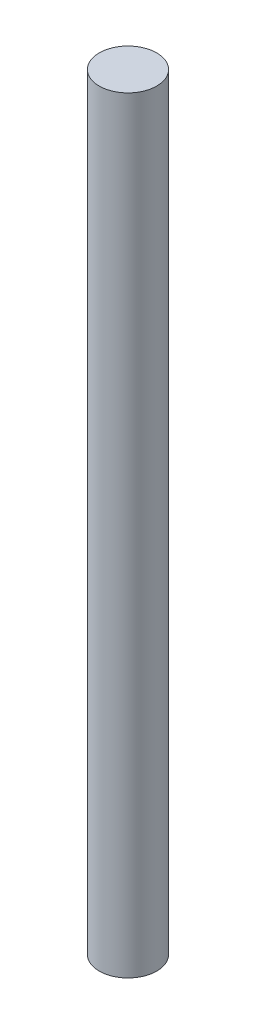
SolidWorks part; units mm, degrees
ref_plane "Front Plane" through (0, 0, 0) normal (0, 0, 1) x (1, 0, 0)
ref_plane "Top Plane" through (0, 0, 0) normal (0, 1, 0) x (1, 0, 0)
ref_plane "Right Plane" through (0, 0, 0) normal (1, 0, 0) x (0, 0, -1)
sketch "Sketch1" plane through (0, 0, 0) normal (0, 1, 0) x (1, 0, 0)
  circle A0 centre (0, 0) radius 1.905
  dimension "D1" = 3.81
extrude "Boss-Extrude1" add sketch "Sketch1" along normal blind 50.8
